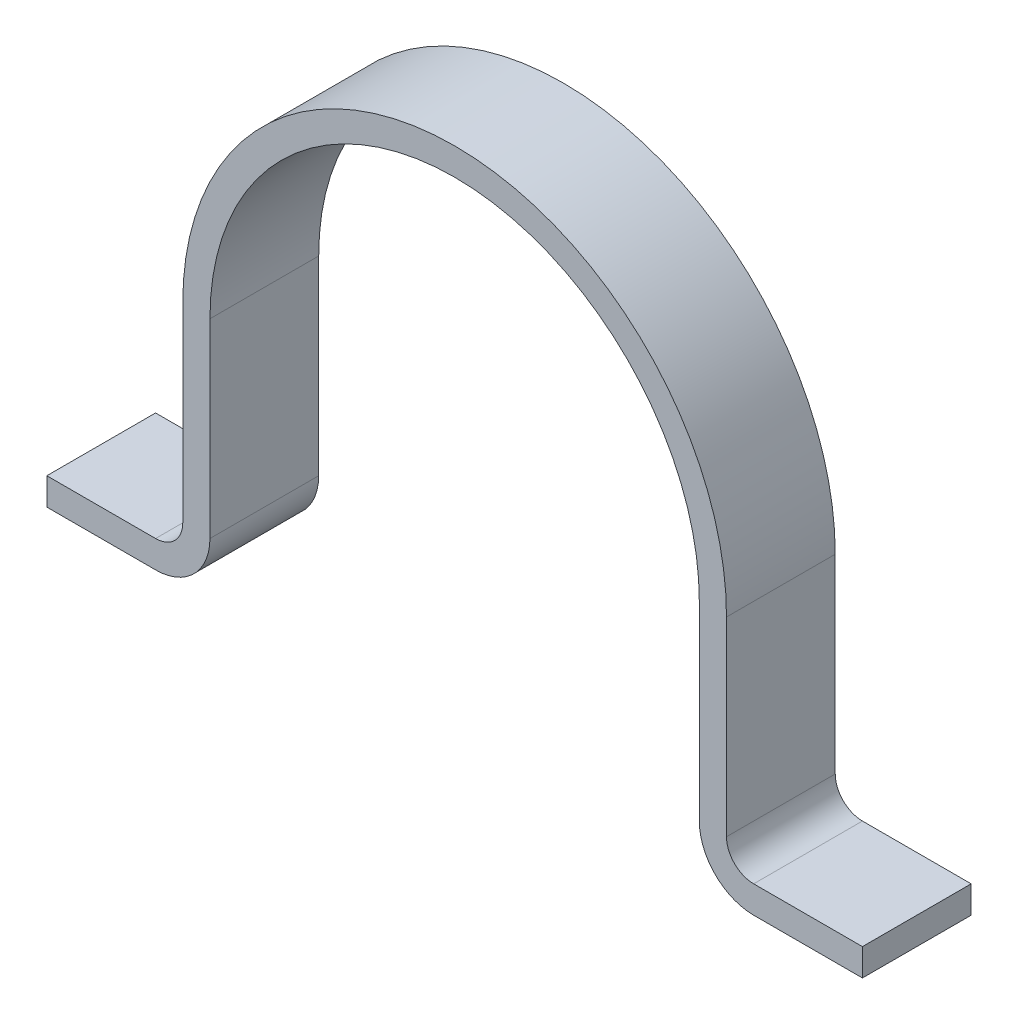
SolidWorks part; units mm, degrees
ref_plane "Front Plane" through (0, 0, 0) normal (0, 0, 1) x (1, 0, 0)
ref_plane "Top Plane" through (0, 0, 0) normal (0, 1, 0) x (1, 0, 0)
ref_plane "Right Plane" through (0, 0, 0) normal (1, 0, 0) x (0, 0, -1)
sketch "Sketch5" plane through (0, 0, 0) normal (0, 0, 1) x (1, 0, 0)
  line L0 (0, 0) -> (45, 0) construction
  line L1 (0, 0) -> (0, -17.5)
  line L2 (45, 0) -> (45, -17.5)
  line L3 (-5, -22.5) -> (-15, -22.5)
  line L4 (50, -22.5) -> (60, -22.5)
  line L5 (50, -20) -> (60, -20)
  line L6 (47.5, -0.0013) -> (47.5, -17.5)
  line L7 (-2.5, -0.0013) -> (-2.5, -17.5)
  line L8 (-5, -20) -> (-15, -20)
  line L9 (-15, -22.5) -> (-15, -20)
  line L10 (60, -22.5) -> (60, -20)
  arc A0 (0, 0) -> (45, 0) centre (22.5, 0.0245) cw
  arc A1 (45, -17.5) -> (50, -22.5) centre (50, -17.5) ccw
  arc A2 (0, -17.5) -> (-5, -22.5) centre (-5, -17.5) cw
  arc A3 (47.5, -17.5) -> (50, -20) centre (50, -17.5) ccw
  arc A4 (-2.5, -0.0013) -> (47.5, -0.0013) centre (22.5, 0.0245) cw
  arc A5 (-2.5, -17.5) -> (-5, -20) centre (-5, -17.5) cw
  point P10 (45, -22.5)
  point P13 (0, -22.5)
  dimension "D6" = 5
  dimension "D1" = 45
  dimension "D2" = 22.5
  dimension "D3" = 22.5
  dimension "D4" = 15
  dimension "D5" = 15
  dimension "D7" = 2.5
extrude "Boss-Extrude3" add sketch "Sketch5" along normal blind 10
